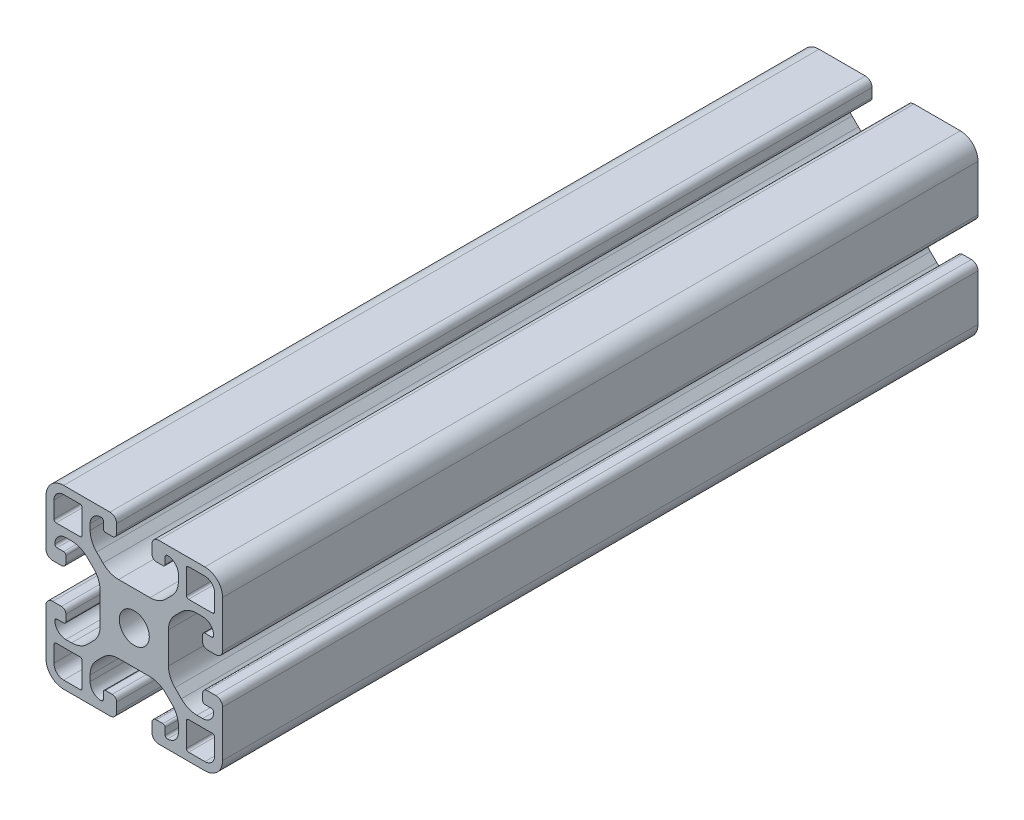
SolidWorks part; units mm, degrees
ref_plane "Plan de face" through (0, 0, 0) normal (0, 0, 1) x (1, 0, 0)
ref_plane "Plan de dessus" through (0, 0, 0) normal (0, 1, 0) x (1, 0, 0)
ref_plane "Plan de droite" through (0, 0, 0) normal (1, 0, 0) x (0, 0, -1)
ref_plane "Plan1" through (0, 0, -30) normal (0, 0, -1) x (-1, 0, 0)
sketch "Esquisse1" plane through (0, 0, -30) normal (0, 0, -1) x (-1, 0, 0)
  line L0 (-4.5, 15) -> (-4.5, 13.5)
  line L1 (-4, 13) -> (-2.5, 13)
  line L2 (-4.5, 10) -> (-5.8076, 10)
  line L3 (-9.3431, 11.4645) -> (-10.7855, 12.9069)
  line L4 (-12.25, 16.4424) -> (-12.25, 23.5576)
  line L5 (-10.7855, 27.0931) -> (-9.3431, 28.5355)
  line L6 (-5.8076, 30) -> (-4.5, 30)
  line L7 (-2.5, 27) -> (-4, 27)
  line L8 (-4.5, 26.5) -> (-4.5, 25)
  line L9 (-3.5, 24) -> (-1.5, 24)
  line L10 (0, 25.5) -> (0, 36)
  line L11 (-4, 40) -> (-14.5, 40)
  line L12 (-16, 38.5) -> (-16, 36.5)
  line L13 (-15, 35.5) -> (-13.5, 35.5)
  line L14 (-13, 36) -> (-13, 37.5)
  line L15 (-10, 35.5) -> (-10, 34.1924)
  line L16 (-11.4645, 30.6569) -> (-12.9069, 29.2145)
  line L17 (-16.4424, 27.75) -> (-23.5576, 27.75)
  line L18 (-27.0931, 29.2145) -> (-28.5355, 30.6569)
  line L19 (-30, 34.1924) -> (-30, 35.5)
  line L20 (-27, 37.5) -> (-27, 36)
  line L21 (-26.5, 35.5) -> (-25, 35.5)
  line L22 (-24, 36.5) -> (-24, 38.5)
  line L23 (-25.5, 40) -> (-36, 40)
  line L24 (-40, 36) -> (-40, 25.5)
  line L25 (-38.5, 24) -> (-36.5, 24)
  line L26 (-35.5, 25) -> (-35.5, 26.5)
  line L27 (-36, 27) -> (-37.5, 27)
  line L28 (-35.5, 30) -> (-34.1924, 30)
  line L29 (-30.6569, 28.5355) -> (-29.2145, 27.0931)
  line L30 (-27.75, 23.5576) -> (-27.75, 16.4424)
  line L31 (-29.2145, 12.9069) -> (-30.6569, 11.4645)
  line L32 (-34.1924, 10) -> (-35.5, 10)
  line L33 (-37.5, 13) -> (-36, 13)
  line L34 (-35.5, 13.5) -> (-35.5, 15)
  line L35 (-36.5, 16) -> (-38.5, 16)
  line L36 (-40, 14.5) -> (-40, 4)
  line L37 (-36, 0) -> (-25.5, 0)
  line L38 (-24, 1.5) -> (-24, 3.5)
  line L39 (-25, 4.5) -> (-26.5, 4.5)
  line L40 (-27, 4) -> (-27, 2.5)
  line L41 (-30, 4.5) -> (-30, 5.8076)
  line L42 (-28.5355, 9.3431) -> (-27.0931, 10.7855)
  line L43 (-23.5576, 12.25) -> (-16.4424, 12.25)
  line L44 (-12.9069, 10.7855) -> (-11.4645, 9.3431)
  line L45 (-10, 5.8076) -> (-10, 4.5)
  line L46 (-13, 2.5) -> (-13, 4)
  line L47 (-13.5, 4.5) -> (-15, 4.5)
  line L48 (-16, 3.5) -> (-16, 1.5)
  line L49 (-14.5, 0) -> (-4, 0)
  line L50 (0, 4) -> (0, 14.5)
  line L51 (-1.5, 16) -> (-3.5, 16)
  line L52 (-4, 1.8) -> (-7.7, 1.8)
  line L53 (-8.2, 2.3) -> (-8.2, 7.7)
  line L54 (-7.7, 8.2) -> (-2.3, 8.2)
  line L55 (-1.8, 7.7) -> (-1.8, 4)
  line L56 (-38.2, 4) -> (-38.2, 7.7)
  line L57 (-37.7, 8.2) -> (-32.3, 8.2)
  line L58 (-31.8, 7.7) -> (-31.8, 2.3)
  line L59 (-32.3, 1.8) -> (-36, 1.8)
  line L60 (-36, 38.2) -> (-32.3, 38.2)
  line L61 (-31.8, 37.7) -> (-31.8, 32.3)
  line L62 (-32.3, 31.8) -> (-37.7, 31.8)
  line L63 (-38.2, 32.3) -> (-38.2, 36)
  line L64 (-1.8, 36) -> (-1.8, 32.3)
  line L65 (-2.3, 31.8) -> (-7.7, 31.8)
  line L66 (-8.2, 32.3) -> (-8.2, 37.7)
  line L67 (-7.7, 38.2) -> (-4, 38.2)
  arc A0 (-4.5, 13.5) -> (-4, 13) centre (-4, 13.5) ccw
  arc A1 (-2.5, 13) -> (-2, 12.5) centre (-2.5, 12.5) cw
  arc A2 (-2, 12.5) -> (-4.5, 10) centre (-4.5, 12.5) cw
  arc A3 (-5.8076, 10) -> (-9.3431, 11.4645) centre (-5.8076, 15) cw
  arc A4 (-10.7855, 12.9069) -> (-12.25, 16.4424) centre (-7.25, 16.4424) cw
  arc A5 (-12.25, 23.5576) -> (-10.7855, 27.0931) centre (-7.25, 23.5576) cw
  arc A6 (-9.3431, 28.5355) -> (-5.8076, 30) centre (-5.8076, 25) cw
  arc A7 (-4.5, 30) -> (-2, 27.5) centre (-4.5, 27.5) cw
  arc A8 (-2, 27.5) -> (-2.5, 27) centre (-2.5, 27.5) cw
  arc A9 (-4, 27) -> (-4.5, 26.5) centre (-4, 26.5) ccw
  arc A10 (-4.5, 25) -> (-3.5, 24) centre (-3.5, 25) ccw
  arc A11 (-1.5, 24) -> (0, 25.5) centre (-1.5, 25.5) ccw
  arc A12 (0, 36) -> (-4, 40) centre (-4, 36) ccw
  arc A13 (-14.5, 40) -> (-16, 38.5) centre (-14.5, 38.5) ccw
  arc A14 (-16, 36.5) -> (-15, 35.5) centre (-15, 36.5) ccw
  arc A15 (-13.5, 35.5) -> (-13, 36) centre (-13.5, 36) ccw
  arc A16 (-13, 37.5) -> (-12.5, 38) centre (-12.5, 37.5) cw
  arc A17 (-12.5, 38) -> (-10, 35.5) centre (-12.5, 35.5) cw
  arc A18 (-10, 34.1924) -> (-11.4645, 30.6569) centre (-15, 34.1924) cw
  arc A19 (-12.9069, 29.2145) -> (-16.4424, 27.75) centre (-16.4424, 32.75) cw
  arc A20 (-23.5576, 27.75) -> (-27.0931, 29.2145) centre (-23.5576, 32.75) cw
  arc A21 (-28.5355, 30.6569) -> (-30, 34.1924) centre (-25, 34.1924) cw
  arc A22 (-30, 35.5) -> (-27.5, 38) centre (-27.5, 35.5) cw
  arc A23 (-27.5, 38) -> (-27, 37.5) centre (-27.5, 37.5) cw
  arc A24 (-27, 36) -> (-26.5, 35.5) centre (-26.5, 36) ccw
  arc A25 (-25, 35.5) -> (-24, 36.5) centre (-25, 36.5) ccw
  arc A26 (-24, 38.5) -> (-25.5, 40) centre (-25.5, 38.5) ccw
  arc A27 (-36, 40) -> (-40, 36) centre (-36, 36) ccw
  arc A28 (-40, 25.5) -> (-38.5, 24) centre (-38.5, 25.5) ccw
  arc A29 (-36.5, 24) -> (-35.5, 25) centre (-36.5, 25) ccw
  arc A30 (-35.5, 26.5) -> (-36, 27) centre (-36, 26.5) ccw
  arc A31 (-37.5, 27) -> (-38, 27.5) centre (-37.5, 27.5) cw
  arc A32 (-38, 27.5) -> (-35.5, 30) centre (-35.5, 27.5) cw
  arc A33 (-34.1924, 30) -> (-30.6569, 28.5355) centre (-34.1924, 25) cw
  arc A34 (-29.2145, 27.0931) -> (-27.75, 23.5576) centre (-32.75, 23.5576) cw
  arc A35 (-27.75, 16.4424) -> (-29.2145, 12.9069) centre (-32.75, 16.4424) cw
  arc A36 (-30.6569, 11.4645) -> (-34.1924, 10) centre (-34.1924, 15) cw
  arc A37 (-35.5, 10) -> (-38, 12.5) centre (-35.5, 12.5) cw
  arc A38 (-38, 12.5) -> (-37.5, 13) centre (-37.5, 12.5) cw
  arc A39 (-36, 13) -> (-35.5, 13.5) centre (-36, 13.5) ccw
  arc A40 (-35.5, 15) -> (-36.5, 16) centre (-36.5, 15) ccw
  arc A41 (-38.5, 16) -> (-40, 14.5) centre (-38.5, 14.5) ccw
  arc A42 (-40, 4) -> (-36, 0) centre (-36, 4) ccw
  arc A43 (-25.5, 0) -> (-24, 1.5) centre (-25.5, 1.5) ccw
  arc A44 (-24, 3.5) -> (-25, 4.5) centre (-25, 3.5) ccw
  arc A45 (-26.5, 4.5) -> (-27, 4) centre (-26.5, 4) ccw
  arc A46 (-27, 2.5) -> (-27.5, 2) centre (-27.5, 2.5) cw
  arc A47 (-27.5, 2) -> (-30, 4.5) centre (-27.5, 4.5) cw
  arc A48 (-30, 5.8076) -> (-28.5355, 9.3431) centre (-25, 5.8076) cw
  arc A49 (-27.0931, 10.7855) -> (-23.5576, 12.25) centre (-23.5576, 7.25) cw
  arc A50 (-16.4424, 12.25) -> (-12.9069, 10.7855) centre (-16.4424, 7.25) cw
  arc A51 (-11.4645, 9.3431) -> (-10, 5.8076) centre (-15, 5.8076) cw
  arc A52 (-10, 4.5) -> (-12.5, 2) centre (-12.5, 4.5) cw
  arc A53 (-12.5, 2) -> (-13, 2.5) centre (-12.5, 2.5) cw
  arc A54 (-13, 4) -> (-13.5, 4.5) centre (-13.5, 4) ccw
  arc A55 (-15, 4.5) -> (-16, 3.5) centre (-15, 3.5) ccw
  arc A56 (-16, 1.5) -> (-14.5, 0) centre (-14.5, 1.5) ccw
  arc A57 (-4, 0) -> (0, 4) centre (-4, 4) ccw
  arc A58 (0, 14.5) -> (-1.5, 16) centre (-1.5, 14.5) ccw
  arc A59 (-3.5, 16) -> (-4.5, 15) centre (-3.5, 15) ccw
  circle A60 centre (-20, 20) radius 3.4
  arc A61 (-1.8, 4) -> (-4, 1.8) centre (-4, 4) cw
  arc A62 (-7.7, 1.8) -> (-8.2, 2.3) centre (-7.7, 2.3) cw
  arc A63 (-8.2, 7.7) -> (-7.7, 8.2) centre (-7.7, 7.7) cw
  arc A64 (-2.3, 8.2) -> (-1.8, 7.7) centre (-2.3, 7.7) cw
  arc A65 (-36, 1.8) -> (-38.2, 4) centre (-36, 4) cw
  arc A66 (-38.2, 7.7) -> (-37.7, 8.2) centre (-37.7, 7.7) cw
  arc A67 (-32.3, 8.2) -> (-31.8, 7.7) centre (-32.3, 7.7) cw
  arc A68 (-31.8, 2.3) -> (-32.3, 1.8) centre (-32.3, 2.3) cw
  arc A69 (-38.2, 36) -> (-36, 38.2) centre (-36, 36) cw
  arc A70 (-32.3, 38.2) -> (-31.8, 37.7) centre (-32.3, 37.7) cw
  arc A71 (-31.8, 32.3) -> (-32.3, 31.8) centre (-32.3, 32.3) cw
  arc A72 (-37.7, 31.8) -> (-38.2, 32.3) centre (-37.7, 32.3) cw
  arc A73 (-4, 38.2) -> (-1.8, 36) centre (-4, 36) cw
  arc A74 (-1.8, 32.3) -> (-2.3, 31.8) centre (-2.3, 32.3) cw
  arc A75 (-7.7, 31.8) -> (-8.2, 32.3) centre (-7.7, 32.3) cw
  arc A76 (-8.2, 37.7) -> (-7.7, 38.2) centre (-7.7, 37.7) cw
extrude "Boss.-Extru.1" add sketch "Esquisse1" against normal blind 171.15
